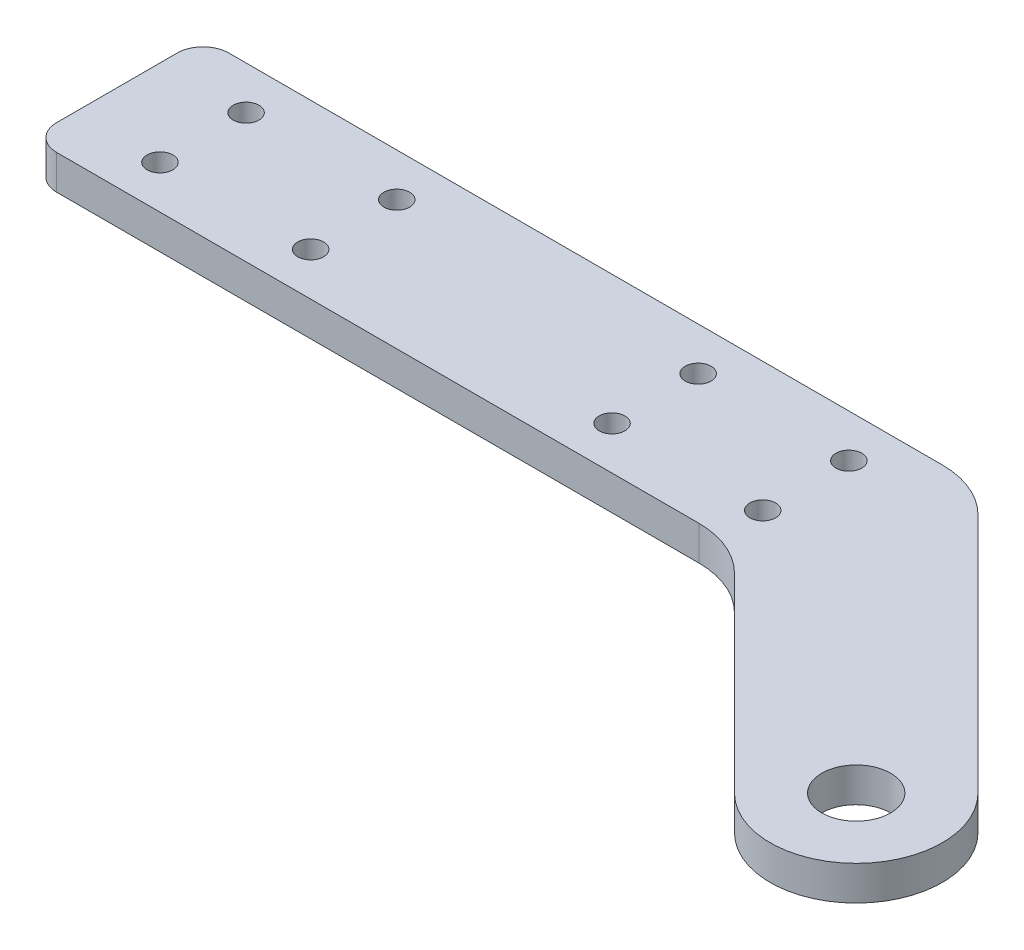
SolidWorks part; units mm, degrees
ref_plane "前视基准面" through (0, 0, 0) normal (0, 0, 1) x (1, 0, 0)
ref_plane "上视基准面" through (0, 0, 0) normal (0, 1, 0) x (1, 0, 0)
ref_plane "右视基准面" through (0, 0, 0) normal (1, 0, 0) x (0, 0, -1)
other "Configuration Table"
sketch "草图1" plane through (0, 0, 0) normal (0, 1, 0) x (1, 0, 0)
  line L0 (61.7157, -20) -> (86.7868, -45.0711)
  line L1 (0, 0) -> (50, 0)
  line L2 (0, 0) -> (0, -20)
  line L3 (0, -20) -> (50, -20)
  line L4 (50, 0) -> (50, -20)
  line L5 (15, 0) -> (35, 0)
  line L6 (15, 0) -> (15, 70)
  line L7 (15, 70) -> (35, 70)
  line L8 (35, 0) -> (35, 70)
  line L9 (50, 0) -> (70, 0)
  line L10 (50, 0) -> (50, -20)
  line L11 (50, -20) -> (70, -20)
  line L12 (70, 0) -> (70, -20)
  line L13 (86.7868, -45.0711) -> (100.9289, -30.9289)
  line L14 (100.9289, -30.9289) -> (70, 0)
  line L16 (0, 0) -> (-20, 0)
  line L17 (0, 0) -> (0, -20)
  line L18 (0, -20) -> (-20, -20)
  line L19 (-20, 0) -> (-20, -20)
  arc A0 (86.7868, -45.0711) -> (100.9289, -30.9289) centre (93.8579, -38) ccw
  circle A2 centre (93.8579, -38) radius 4
  dimension "D9" = 18
  dimension "D7" = 8
  dimension "D8" = 10
  dimension "D1" = 20
  dimension "D2" = 50
  dimension "D3" = 20
  dimension "D4" = 15
  dimension "D5" = 70
  dimension "D6" = 20
  dimension "D10" = 45
  dimension "D11" = 20
extrude "凸台-拉伸1" add sketch "草图1" along normal blind 4
sketch "草图2" plane through (0, 4, 0) normal (0, 1, 0) x (1, 0, 0)
  line L0 (15, 0) -> (15, 70) construction
  line L1 (15, 70) -> (35, 70) construction
  line L2 (17.5, 60) -> (32.5, 60) construction
  line L3 (17.5, 60) -> (17.5, 50) construction
  line L4 (17.5, 60) -> (17.5, 20) construction
  line L6 (35, 0) -> (70, 0) construction
  line L7 (-20, -20) -> (61.7157, -20) construction
  line L8 (25, -20) -> (25, 70) construction
  line L9 (50, 0) -> (50, -20) construction
  line L10 (35, 0) -> (70, 0) construction
  line L11 (-20, -20) -> (61.7157, -20) construction
  circle A0 centre (17.5, 60) radius 1.5
  circle A1 centre (32.5, 60) radius 1.5
  circle A2 centre (32.5, 50) radius 1.5
  circle A3 centre (17.5, 50) radius 1.5
  circle A4 centre (17.5, 20) radius 1.5
  circle A5 centre (17.5, 10) radius 1.5
  circle A6 centre (32.5, 10) radius 1.5
  circle A7 centre (32.5, 20) radius 1.5
  circle A8 centre (42.5, -5) radius 1.5
  circle A9 centre (42.5, -15) radius 1.5
  circle A10 centre (7.5, -15) radius 1.5
  circle A11 centre (7.5, -5) radius 1.5
  circle A12 centre (60, -15) radius 1.5
  circle A13 centre (60, -5) radius 1.5
  circle A14 centre (-10, -15) radius 1.5
  circle A15 centre (-10, -5) radius 1.5
  dimension "D1" = 3
  dimension "D2" = 2.5
  dimension "D3" = 10
  dimension "D8" = 10
  dimension "D11" = 3
  dimension "D12" = 7.5
  dimension "D13" = 5
  dimension "D14" = 5
  dimension "D17" = 17.5
  dimension "D6" = 90
  dimension "D7" = 15
  dimension "D10" = 40
  dimension "D15" = 20
  dimension "D16" = 2
  dimension "D4" = 2
  dimension "D5" = 2
  dimension "D9" = 2
extrude "切除-拉伸1" cut sketch "草图2" against normal up to next
sketch "草图3" plane through (0, 4, 0) normal (0, 1, 0) x (1, 0, 0)
  line L0 (50, 0) -> (35, 0)
  line L1 (35, 0) -> (35, 20)
  line L2 (35, 0) -> (35, 70) construction
  line L3 (35, 20) -> (50, 0)
  line L4 (15, 0) -> (0, 0)
  line L5 (0, 0) -> (15, 20)
  line L6 (15, 0) -> (15, 70) construction
  line L7 (15, 20) -> (15, 0)
  dimension "D1" = 20
  dimension "D2" = 15
extrude "凸台-拉伸2" add sketch "草图3" against normal up to surface (4 mm away) up to face at (17.5, 0, -8.5)
fillet "圆角1" radius 3 8 edges at (35, 2, -70) (15, 2, -70) (15, 2, -20) (50, 2, 0) (35, 2, -20) (-20, 2, 20) (0, 2, 0) (-20, 2, 0)
fillet "圆角3" radius 10 2 edges at (70, 2, 0) (61.7157, 2, 20)
sketch "草图4" plane through (0, 4, 0) normal (0, 1, 0) x (1, 0, 0)
  line L0 (-1.5, 0) -> (51.5, 0)
  line L12 (100.9289, -30.9289) -> (72.9289, -2.9289)
  line L13 (65.8579, 0) -> (51.5, 0)
  line L14 (49.1, 1.2) -> (35.6, 19.2)
  line L15 (35, 21) -> (35, 67)
  line L16 (32, 70) -> (18, 70)
  line L17 (15, 67) -> (15, 21)
  line L18 (14.4, 19.2) -> (0.9, 1.2)
  line L19 (-1.5, 0) -> (-17, 0)
  line L20 (-20, -3) -> (-20, -17)
  line L21 (-17, -20) -> (57.5736, -20)
  line L22 (64.6447, -22.9289) -> (86.7868, -45.0711)
  line L23 (100.9289, -30.9289) -> (72.9289, -2.9289)
  line L24 (65.8579, 0) -> (51.5, 0)
  line L25 (49.1, 1.2) -> (35.6, 19.2)
  line L26 (35, 21) -> (35, 67)
  line L27 (32, 70) -> (18, 70)
  line L28 (15, 67) -> (15, 21)
  line L29 (14.4, 19.2) -> (0.9, 1.2)
  line L30 (-1.5, 0) -> (-17, 0)
  line L31 (-20, -3) -> (-20, -17)
  line L32 (-17, -20) -> (57.5736, -20)
  line L33 (64.6447, -22.9289) -> (86.7868, -45.0711)
  arc A11 (72.9289, -2.9289) -> (65.8579, 0) centre (65.8579, -10) ccw
  arc A12 (49.1, 1.2) -> (51.5, 0) centre (51.5, 3) ccw
  arc A13 (35, 21) -> (35.6, 19.2) centre (38, 21) ccw
  arc A14 (35, 67) -> (32, 70) centre (32, 67) ccw
  arc A15 (18, 70) -> (15, 67) centre (18, 67) ccw
  arc A16 (14.4, 19.2) -> (15, 21) centre (12, 21) ccw
  arc A17 (-1.5, 0) -> (0.9, 1.2) centre (-1.5, 3) ccw
  arc A18 (-17, 0) -> (-20, -3) centre (-17, -3) ccw
  arc A19 (-20, -17) -> (-17, -20) centre (-17, -17) ccw
  arc A20 (64.6447, -22.9289) -> (57.5736, -20) centre (57.5736, -30) ccw
  arc A21 (86.7868, -45.0711) -> (100.9289, -30.9289) centre (93.8579, -38) ccw
  arc A22 (72.9289, -2.9289) -> (65.8579, 0) centre (65.8579, -10) ccw
  arc A23 (49.1, 1.2) -> (51.5, 0) centre (51.5, 3) ccw
  arc A24 (35, 21) -> (35.6, 19.2) centre (38, 21) ccw
  arc A25 (35, 67) -> (32, 70) centre (32, 67) ccw
  arc A26 (18, 70) -> (15, 67) centre (18, 67) ccw
  arc A27 (14.4, 19.2) -> (15, 21) centre (12, 21) ccw
  arc A28 (-1.5, 0) -> (0.9, 1.2) centre (-1.5, 3) ccw
  arc A29 (-17, 0) -> (-20, -3) centre (-17, -3) ccw
  arc A30 (-20, -17) -> (-17, -20) centre (-17, -17) ccw
  arc A31 (64.6447, -22.9289) -> (57.5736, -20) centre (57.5736, -30) ccw
  arc A32 (86.7868, -45.0711) -> (100.9289, -30.9289) centre (93.8579, -38) ccw
  arc M26 (51.5, 0) -> (49.1, 1.2) centre (51.5, 3) cw
  line M27 (49.1, 1.2) -> (35.6, 19.2)
  arc M28 (35.6, 19.2) -> (35, 21) centre (38, 21) cw
  line M29 (35, 21) -> (35, 67)
  arc M30 (35, 67) -> (32, 70) centre (32, 67) ccw
  line M31 (32, 70) -> (18, 70)
  arc M32 (18, 70) -> (15, 67) centre (18, 67) ccw
  line M33 (15, 67) -> (15, 21)
  arc M34 (15, 21) -> (14.4, 19.2) centre (12, 21) cw
  line M35 (14.4, 19.2) -> (0.9, 1.2)
  arc M36 (0.9, 1.2) -> (-1.5, 0) centre (-1.5, 3) cw
  circle M45 centre (17.5, 10) radius 1.5
  circle M46 centre (32.5, 10) radius 1.5
  circle M47 centre (32.5, 20) radius 1.5
  circle M48 centre (17.5, 20) radius 1.5
  circle M50 centre (32.5, 60) radius 1.5
  circle M51 centre (32.5, 50) radius 1.5
  circle M52 centre (17.5, 50) radius 1.5
  circle M60 centre (17.5, 60) radius 1.5
  dimension "D1" = 0
extrude "切除-拉伸2" cut sketch "草图4" against normal blind 10 contours L0 M36 M26 M27 M28 M29 M30 M31 M32 M33 M34 M35 M46 M48 M50 M52 M60 M51 M47 M45
